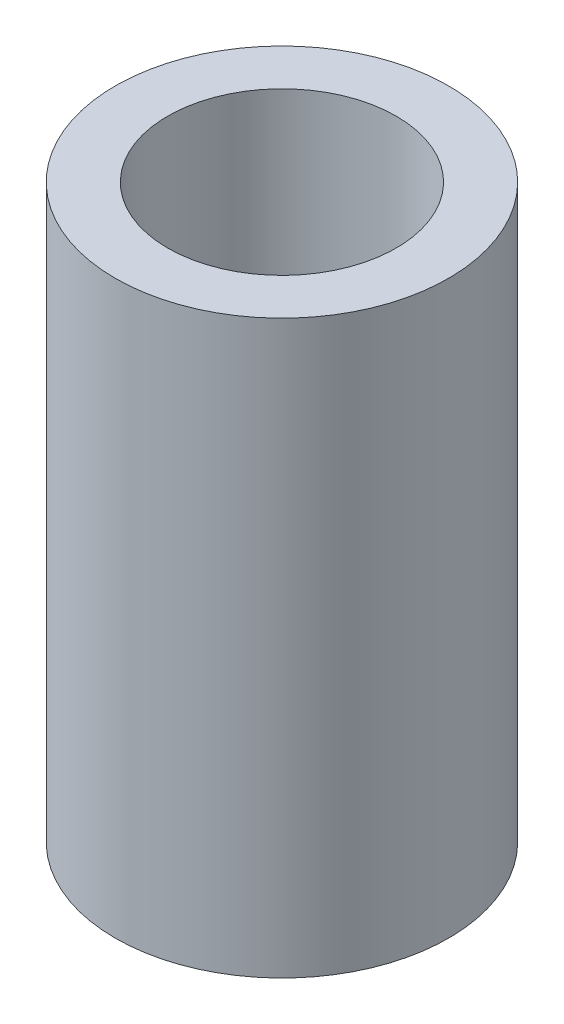
SolidWorks part; units mm, degrees
ref_plane "Front Plane" through (0, 0, 0) normal (0, 0, 1) x (1, 0, 0)
ref_plane "Top Plane" through (0, 0, 0) normal (0, 1, 0) x (1, 0, 0)
ref_plane "Right Plane" through (0, 0, 0) normal (1, 0, 0) x (0, 0, -1)
sketch "Sketch1" plane through (0, 0, 0) normal (0, 1, 0) x (1, 0, 0)
  circle A0 centre (0, 0) radius 1.75
  circle A1 centre (0, 0) radius 1.2
  dimension "D1" = 2.4
  dimension "D2" = 3.5
extrude "Boss-Extrude1" add sketch "Sketch1" along normal blind 6
